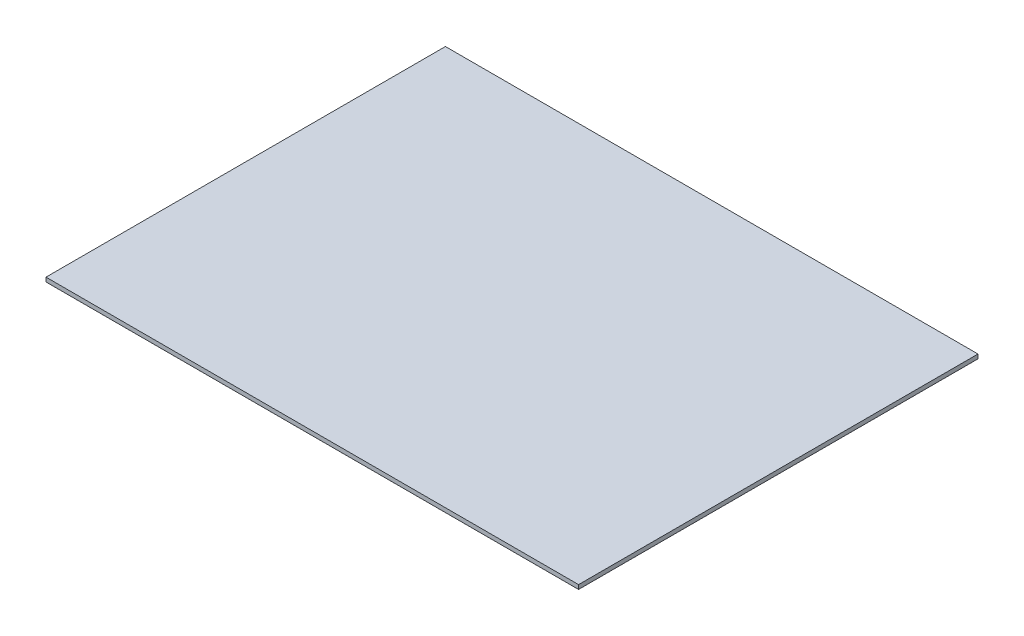
SolidWorks part; units mm, degrees
ref_plane "Front Plane" through (0, 0, 0) normal (0, 0, 1) x (1, 0, 0)
ref_plane "Top Plane" through (0, 0, 0) normal (0, 1, 0) x (1, 0, 0)
ref_plane "Right Plane" through (0, 0, 0) normal (1, 0, 0) x (0, 0, -1)
sketch "Sketch1" plane through (0, 0, 0) normal (0, 1, 0) x (1, 0, 0)
  line L1 (-50.8, -38.1) -> (50.8, -38.1)
  line L2 (-50.8, -38.1) -> (-50.8, 38.1)
  line L3 (-50.8, 38.1) -> (50.8, 38.1)
  line L4 (50.8, -38.1) -> (50.8, 38.1)
  line L5 (-50.8, -38.1) -> (50.8, 38.1) construction
  line L6 (-50.8, 38.1) -> (50.8, -38.1) construction
  point P0 (0, 0)
  dimension "D1" = 76.2
  dimension "D2" = 101.6
extrude "Boss-Extrude1" add sketch "Sketch1" along normal blind 0.7874
sketch "Sketch2" plane through (0, 0, 0) normal (0, -1, 0) x (1, 0, 0)
  line L4 (50.8, -38.1) -> (50.8, 38.1)
  line L5 (50.8, 38.1) -> (-50.8, 38.1)
  line L6 (-50.8, 38.1) -> (-50.8, -38.1)
  line L7 (-50.8, -38.1) -> (50.8, -38.1)
  line L8 (50.8, -38.1) -> (50.8, 38.1)
  line L9 (50.8, 38.1) -> (-50.8, 38.1)
  line L10 (-50.8, 38.1) -> (-50.8, -38.1)
  line L11 (-50.8, -38.1) -> (50.8, -38.1)
  dimension "D1" = 0
extrude "Boss-Extrude2" add sketch "Sketch2" along normal blind 0.0174 separate body
sketch "Sketch3" plane through (0, 0.7874, 0) normal (0, 1, 0) x (1, 0, 0)
  line L0 (-31.3339, 23.5551) -> (-30.4957, 23.5551) construction
  line L1 (-39.8266, 24.3425) -> (-35.8174, 24.3425)
  line L2 (-33.2148, 23.5551) -> (-39.9633, 23.5551) construction
  line L3 (-39.8706, 22.7677) -> (-35.8174, 22.7677)
  line L4 (-33.2148, 23.5551) -> (-36.589, 29.3994) construction
  line L5 (-37.2246, 28.9255) -> (-35.198, 25.4153)
  line L6 (-35.8388, 29.6748) -> (-33.8342, 26.2027)
  line L7 (-33.2148, 23.5551) -> (-29.8406, 29.3994) construction
  line L8 (-30.5688, 29.7129) -> (-32.5954, 26.2027)
  line L9 (-29.227, 28.8874) -> (-31.2316, 25.4153)
  line L10 (-33.2148, 23.5551) -> (-26.4664, 23.5551) construction
  line L11 (-26.559, 24.3425) -> (-30.6122, 24.3425)
  line L12 (-26.603, 22.7677) -> (-30.6122, 22.7677)
  line L13 (-33.2148, 23.5551) -> (-35.8174, 22.7677) construction
  line L14 (-33.2148, 23.5551) -> (-35.198, 25.4153) construction
  circle A0 centre (-33.2148, 23.5551) radius 2.3 construction
  circle A1 centre (-33.2148, 23.5551) radius 2.7191
  circle A2 centre (-33.2148, 23.5551) radius 1.8809
  point P6 (-30.9148, 23.5551)
  dimension "D1" = 4.6
  dimension "D2" = 0.8382
  dimension "D3" = 1.5748
  dimension "D5" = 60
  dimension "D4" = 4
